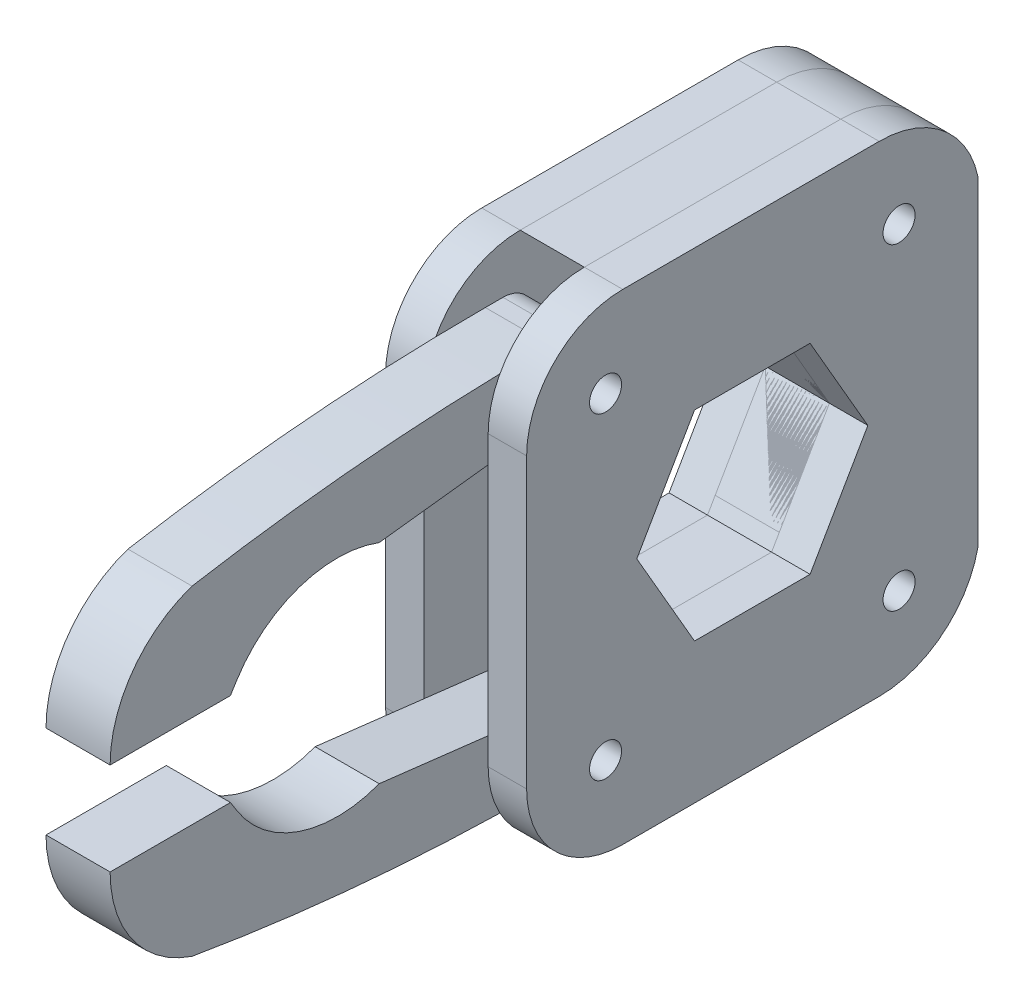
SolidWorks part; units mm, degrees
material "Alumina"
ref_plane "Front Plane" through (0, 0, 0) normal (1, 0, 0) x (0, 1, 0)
ref_plane "Top Plane" through (0, 0, 0) normal (0, 0, 1) x (0, 1, 0)
ref_plane "Right Plane" through (0, 0, 0) normal (0, 1, 0) x (-1, 0, 0)
sketch "Sketch1" plane through (0, 0, 0) normal (1, 0, 0) x (0, 1, 0)
  circle A0 centre (0, 0) radius 10
  dimension "D1" = 20
extrude "Boss-Extrude1" add sketch "Sketch1" against normal blind 10
sketch "Sketch2" plane through (0, 0, 0) normal (0, 0, 1) x (0, 1, 0)
  line L0 (10, 10) -> (-10, 10) construction
  line L1 (-50, 10) -> (50, 10)
  line L2 (-50, 10) -> (-50, 60)
  line L3 (-50, 60) -> (50, 60)
  line L4 (50, 10) -> (50, 60)
  point P7 (0, 10)
  dimension "D1" = 100
  dimension "D2" = 50
extrude "Boss-Extrude2" add sketch "Sketch2" against normal mid plane 20
sketch "Sketch3" plane through (0, 0, 10) normal (0, 0, 1) x (1, 0, 0)
  line L0 (-150.832, 45) -> (-150.832, -45)
  line L1 (-120.832, -75) -> (-40.832, -75)
  line L5 (-40.832, 75) -> (-120.832, 75)
  line L6 (-126.2072, 49.5282) -> (-126.2072, -49.5282) construction
  line L7 (-120.832, 45) -> (-126.2072, 49.5282) construction
  line L8 (-120.832, -45) -> (-126.2072, -49.5282) construction
  line L10 (-10, -50) -> (-10, 50)
  circle A0 centre (-126.2072, 49.5282) radius 5
  circle A1 centre (-126.2072, -49.5282) radius 5
  arc A2 (-150.832, -45) -> (-120.832, -75) centre (-120.832, -45) ccw
  arc A5 (-120.832, 75) -> (-150.832, 45) centre (-120.832, 45) ccw
  arc A6 (-40.832, 75) -> (-10, 50) centre (-40.832, 43.4878) cw
  arc A7 (-40.832, -75) -> (-10, -50) centre (-40.832, -43.4878) ccw
  point P1 (-150.832, 0)
  dimension "D5" = 10
  dimension "D6" = 30
  dimension "D1" = 80
  dimension "D2" = 90
extrude "Boss-Extrude3" add sketch "Sketch3" along normal blind 12 separate body
sketch "Sketch4" plane through (0, 0, -10) normal (0, 0, -1) x (1, 0, 0)
  line L0 (-10, 50) -> (-10, -50)
  line L5 (-10, -50) -> (-10, 50)
  line L6 (-10, -50) -> (-10, 50)
  line L11 (-40.832, 75) -> (-120.832, 75)
  line L12 (-150.832, 45) -> (-150.832, -45)
  line L13 (-120.832, -75) -> (-40.832, -75)
  line L19 (-40.832, 75) -> (-120.832, 75)
  line L20 (-150.832, 45) -> (-150.832, -45)
  line L21 (-120.832, -75) -> (-40.832, -75)
  arc A4 (-10, 50) -> (-40.832, 75) centre (-40.832, 43.4878) ccw
  arc A5 (-120.832, 75) -> (-150.832, 45) centre (-120.832, 45) ccw
  arc A6 (-150.832, -45) -> (-120.832, -75) centre (-120.832, -45) ccw
  arc A7 (-10, 50) -> (-40.832, 75) centre (-40.832, 43.4878) ccw
  arc A9 (-120.832, 75) -> (-150.832, 45) centre (-120.832, 45) ccw
  arc A10 (-150.832, -45) -> (-120.832, -75) centre (-120.832, -45) ccw
  arc A12 (-40.832, -75) -> (-10, -50) centre (-40.832, -43.4878) ccw
  arc A13 (-40.832, -75) -> (-10, -50) centre (-40.832, -43.4878) ccw
  line M14 (-10, 50) -> (-60, 50)
  line M15 (-60, 50) -> (-60, -50)
  line M16 (-60, -50) -> (-10, -50)
  line M17 (-10, -50) -> (-10, 0)
  line M19 (-10, 0) -> (-10, 50)
  dimension "D1" = 0
extrude "Boss-Extrude4" add sketch "Sketch4" along normal blind 12 separate body contours L21 A13 A7 L19 A9 L20 A10 M16 M15 M14 | M19 M14 M15 M16 M17
sketch "Sketch6" plane through (0, 0, 10) normal (0, 0, -1) x (1, 0, 0)
  line L4 (-126.2072, -39.5282) -> (-184.8266, -32.5736)
  line L5 (-131.7162, -59.5282) -> (-126.2072, -59.5282)
  line L6 (-10, 0) -> (-113.6893, 0) construction
  line L10 (-268.7893, -14.4446) -> (-231.2479, -14.4446)
  line L12 (-231.2479, -14.4446) -> (-229.2699, -17.6029)
  line L14 (-231.2479, 14.4446) -> (-229.2699, 17.6029)
  line L15 (-268.7893, 14.4446) -> (-231.2479, 14.4446)
  line L17 (-131.7162, 59.5282) -> (-126.2072, 59.5282)
  line L18 (-126.2072, 39.5282) -> (-184.8266, 32.5736)
  arc A0 (-126.2072, -59.5282) -> (-126.2072, -39.5282) centre (-126.2072, -49.5282) ccw
  arc A12 (-131.7162, -59.5282) -> (-243.2317, -50.0219) centre (-131.7162, 599.3036) cw
  arc A13 (-243.2317, -50.0219) -> (-268.7893, -14.4446) centre (-231.2479, -14.4446) cw
  arc A14 (-229.2699, -17.6029) -> (-184.8266, -32.5736) centre (-197.9114, 2.0361) ccw
  arc A15 (-229.2699, 17.6029) -> (-184.8266, 32.5736) centre (-197.9114, -2.0361) cw
  arc A16 (-243.2317, 50.0219) -> (-268.7893, 14.4446) centre (-231.2479, 14.4446) ccw
  arc A17 (-131.7162, 59.5282) -> (-243.2317, 50.0219) centre (-131.7162, -599.3036) ccw
  arc A19 (-126.2072, 59.5282) -> (-126.2072, 39.5282) centre (-126.2072, 49.5282) cw
  dimension "D2" = 20
extrude "Boss-Extrude5" add sketch "Sketch6" along normal up to surface (20 mm away) separate body up to face at (-81.0695, 0, -10)
sketch "Sketch8" plane through (0, 0, 22) normal (0, 0, 1) x (1, 0, 0)
  circle A1 centre (-126.2072, 49.5282) radius 5
  circle A3 centre (-126.2072, -49.5282) radius 5
  circle M7 centre (-126.2072, 49.5282) radius 5
  circle M20 centre (-126.2072, -49.5282) radius 5
extrude "Cut-Extrude4" cut sketch "Sketch8" against normal through all both and the other way through all contours M20 | M7
sketch "Sketch9" plane through (0, 0, 0) normal (1, 0, 0) x (0, 1, 0)
  line L1 (-2.5, 2.5) -> (2.5, 2.5)
  line L2 (-2.5, 2.5) -> (-2.5, -2.5)
  line L3 (-2.5, -2.5) -> (2.5, -2.5)
  line L4 (2.5, 2.5) -> (2.5, -2.5)
  line L5 (-2.5, 2.5) -> (2.5, -2.5) construction
  line L6 (-2.5, -2.5) -> (2.5, 2.5) construction
  point P0 (0, 0)
  dimension "D1" = 5
  dimension "D2" = 5
extrude "Cut-Extrude6" cut sketch "Sketch9" against normal blind 10
sketch "Sketch10" plane through (0, 0, 22) normal (0, 0, 1) x (0, -1, 0)
  line L0 (0, -116.4609) -> (0, -44.3711) construction
  line L2 (-49.5282, -34.6247) -> (49.5282, -34.6247) construction
  line L3 (-49.5282, -34.6247) -> (-49.5282, -126.2072) construction
  line L4 (-49.5282, -126.2072) -> (49.5282, -126.2072) construction
  line L5 (49.5282, -34.6247) -> (49.5282, -126.2072) construction
  line L6 (-49.5282, -34.6247) -> (49.5282, -126.2072) construction
  line L7 (-49.5282, -126.2072) -> (49.5282, -34.6247) construction
  point P4 (0, -80.416)
sketch "Sketch11" plane through (0, 0, 10) normal (0, 0, -1) x (0, 1, 0)
  line L1 (23.4955, -126.2072) -> (-23.4955, -126.2072)
  line L6 (75, -120.832) -> (75, -40.832)
  line L7 (50, -10) -> (-50, -10)
  line L8 (-75, -40.832) -> (-75, -120.832)
  line L9 (-45, -150.832) -> (45, -150.832)
  line L10 (75, -120.832) -> (75, -40.832)
  line L11 (50, -10) -> (-50, -10)
  line L12 (-75, -40.832) -> (-75, -120.832)
  arc A0 (-75, -120.832) -> (-23.4955, -126.2072) centre (-49.5282, -126.2072) cw
  arc A2 (75, -120.832) -> (23.4955, -126.2072) centre (49.5282, -126.2072) ccw
  arc A8 (45, -150.832) -> (75, -120.832) centre (45, -120.832) ccw
  arc A9 (75, -40.832) -> (50, -10) centre (43.4878, -40.832) ccw
  arc A10 (-50, -10) -> (-75, -40.832) centre (-43.4878, -40.832) ccw
  arc A11 (-75, -120.832) -> (-45, -150.832) centre (-45, -120.832) ccw
  arc A13 (75, -40.832) -> (50, -10) centre (43.4878, -40.832) ccw
  arc A14 (-50, -10) -> (-75, -40.832) centre (-43.4878, -40.832) ccw
  dimension "D1" = 0
extrude "Boss-Extrude6" add sketch "Sketch11" along normal up to surface (20 mm away) separate body up to face at (-131.2072, -49.5282, -10)
sketch "Sketch7" plane through (0, 0, 22) normal (0, 0, 1) x (1, 0, 0)
  line L0 (-10, 0) -> (-150.832, 0) construction
  line L1 (-10, -50) -> (-10, 50) construction
  line L2 (-150.832, 45) -> (-150.832, -45) construction
  line L4 (-44.3711, 0) -> (-62.3935, 31.2158)
  line L5 (-62.3935, 31.2158) -> (-98.4384, 31.2158)
  line L6 (-98.4384, 31.2158) -> (-116.4609, 0)
  line L7 (-116.4609, 0) -> (-98.4384, -31.2158)
  line L8 (-98.4384, -31.2158) -> (-62.3935, -31.2158)
  line L9 (-62.3935, -31.2158) -> (-44.3711, 0)
  circle A0 centre (-80.416, 0) radius 31.2158 construction
extrude "Cut-Extrude5" cut sketch "Sketch7" against normal through all contours L8 L9 L4 L5 L6 L7
pattern_linear "LPattern1" count 2 spacing 91.5825 along (1, 0, 0) of "Cut-Extrude4"
sketch "Sketch12" plane through (0, 0, -10) normal (0, 0, -1) x (1, 0, 0)
  circle A0 centre (-34.6247, -49.5282) radius 5 construction
  circle A1 centre (-34.6247, 49.5282) radius 5 construction
  circle A2 centre (-34.6247, -49.5282) radius 5
  circle A3 centre (-34.6247, 49.5282) radius 5
extrude "Cut-Extrude7" cut sketch "Sketch12" against normal through all both and the other way through all
sketch "Sketch13" plane through (0, 0, 0) normal (1, 0, 0) x (0, 1, 0)
  line L0 (0, 0) -> (101.0817, 0) construction
  line L1 (0, 0) -> (0, 60.4692) construction
move or copy body "Body-Move/Copy1" bodies to move or copy 126 124 127 123 120 131 copy no rotation origin (0, 0, 0) rotation axis (0, 1, 0) rotation angle 90 parameters "Angle Around Edge"=90
